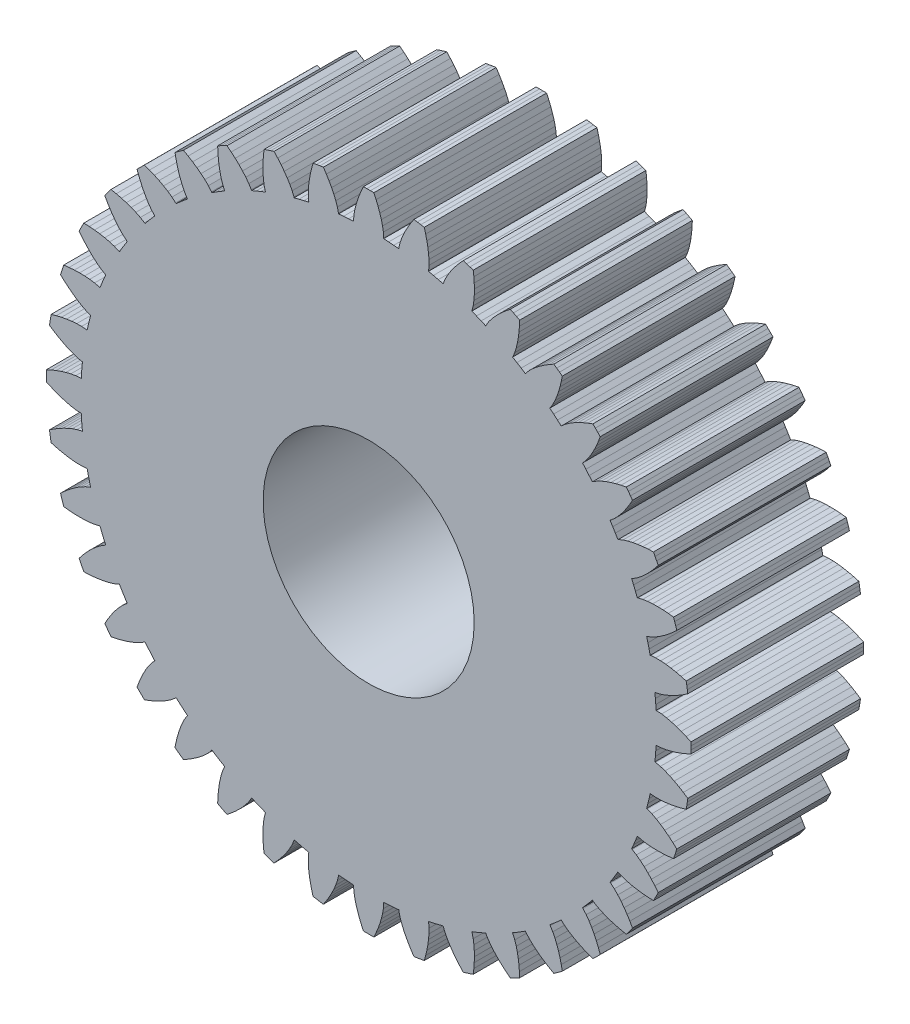
SolidWorks part; units mm, degrees
ref_plane "Спереди" through (0, 0, 0) normal (0, 0, 1) x (1, 0, 0)
ref_plane "Сверху" through (0, 0, 0) normal (0, 1, 0) x (1, 0, 0)
ref_plane "Справа" through (0, 0, 0) normal (1, 0, 0) x (0, 0, -1)
sketch "Эскиз1" plane through (0, 0, 0) normal (0, 0, 1) x (1, 0, 0)
  line L0 (29.959, -1.5683) -> (30.029, -1.5719)
  line L1 (30.029, -1.5719) -> (30.5358, -1.5362)
  line L2 (30.5358, -1.5362) -> (31.045, -1.4475)
  line L3 (31.045, -1.4475) -> (31.5552, -1.3227)
  line L4 (31.5552, -1.3227) -> (32.066, -1.1675)
  line L5 (32.066, -1.1675) -> (32.5766, -0.9849)
  line L6 (32.5766, -0.9849) -> (33.0866, -0.7771)
  line L7 (33.0866, -0.7771) -> (33.5956, -0.5455)
  line L8 (33.5956, -0.5455) -> (33.5995, -0.1818)
  line L9 (33.5995, -0.1818) -> (33.5995, 0.1818)
  line L10 (33.5995, 0.1818) -> (33.5956, 0.5455)
  line L11 (33.5956, 0.5455) -> (33.0866, 0.7771)
  line L12 (33.0866, 0.7771) -> (32.5766, 0.9849)
  line L13 (32.5766, 0.9849) -> (32.066, 1.1675)
  line L14 (32.066, 1.1675) -> (31.5552, 1.3227)
  line L15 (31.5552, 1.3227) -> (31.045, 1.4475)
  line L16 (31.045, 1.4475) -> (30.5358, 1.5362)
  line L17 (30.5358, 1.5362) -> (30.029, 1.5719)
  line L18 (30.029, 1.5719) -> (29.959, 1.5683)
  line L19 (29.959, 1.5683) -> (29.927, 2.0921)
  line L20 (29.927, 2.0921) -> (29.8858, 2.6153)
  line L21 (29.8858, 2.6153) -> (29.8355, 3.1377)
  line L22 (29.8355, 3.1377) -> (29.9052, 3.145)
  line L23 (29.9052, 3.145) -> (30.4002, 3.2595)
  line L24 (30.4002, 3.2595) -> (30.8892, 3.4268)
  line L25 (30.8892, 3.4268) -> (31.3737, 3.6299)
  line L26 (31.3737, 3.6299) -> (31.8538, 3.8631)
  line L27 (31.8538, 3.8631) -> (32.3296, 4.1233)
  line L28 (32.3296, 4.1233) -> (32.8008, 4.4083)
  line L29 (32.8008, 4.4083) -> (33.2673, 4.7167)
  line L30 (33.2673, 4.7167) -> (33.2143, 5.0765)
  line L31 (33.2143, 5.0765) -> (33.1574, 5.4357)
  line L32 (33.1574, 5.4357) -> (33.0966, 5.7943)
  line L33 (33.0966, 5.7943) -> (32.5577, 5.9435)
  line L34 (32.5577, 5.9435) -> (32.0214, 6.0689)
  line L35 (32.0214, 6.0689) -> (31.4885, 6.1693)
  line L36 (31.4885, 6.1693) -> (30.9598, 6.2428)
  line L37 (30.9598, 6.2428) -> (30.4363, 6.2862)
  line L38 (30.4363, 6.2862) -> (29.9195, 6.2942)
  line L39 (29.9195, 6.2942) -> (29.4134, 6.2502)
  line L40 (29.4134, 6.2502) -> (29.3448, 6.2356)
  line L41 (29.3448, 6.2356) -> (29.2312, 6.7479)
  line L42 (29.2312, 6.7479) -> (29.1087, 7.2582)
  line L43 (29.1087, 7.2582) -> (28.9773, 7.7663)
  line L44 (28.9773, 7.7663) -> (29.0451, 7.7845)
  line L45 (29.0451, 7.7845) -> (29.516, 7.975)
  line L46 (29.516, 7.975) -> (29.9728, 8.2167)
  line L47 (29.9728, 8.2167) -> (30.4196, 8.4931)
  line L48 (30.4196, 8.4931) -> (30.8573, 8.7986)
  line L49 (30.8573, 8.7986) -> (31.2865, 9.13)
  line L50 (31.2865, 9.13) -> (31.7074, 9.4852)
  line L51 (31.7074, 9.4852) -> (32.1199, 9.8628)
  line L52 (32.1199, 9.8628) -> (32.0112, 10.2099)
  line L53 (32.0112, 10.2099) -> (31.8988, 10.5558)
  line L54 (31.8988, 10.5558) -> (31.7827, 10.9004)
  line L55 (31.7827, 10.9004) -> (31.2271, 10.9634)
  line L56 (31.2271, 10.9634) -> (30.6778, 11.0035)
  line L57 (30.6778, 11.0035) -> (30.1358, 11.0193)
  line L58 (30.1358, 11.0193) -> (29.6021, 11.0091)
  line L59 (29.6021, 11.0091) -> (29.0782, 10.9701)
  line L60 (29.0782, 10.9701) -> (28.5666, 10.8971)
  line L61 (28.5666, 10.8971) -> (28.0736, 10.7745)
  line L62 (28.0736, 10.7745) -> (28.0081, 10.7493)
  line L63 (28.0081, 10.7493) -> (27.8157, 11.2376)
  line L64 (27.8157, 11.2376) -> (27.6149, 11.7225)
  line L65 (27.6149, 11.7225) -> (27.4056, 12.2038)
  line L66 (27.4056, 12.2038) -> (27.4697, 12.2323)
  line L67 (27.4697, 12.2323) -> (27.905, 12.4942)
  line L68 (27.905, 12.4942) -> (28.3184, 12.8043)
  line L69 (28.3184, 12.8043) -> (28.7164, 13.1472)
  line L70 (28.7164, 13.1472) -> (29.101, 13.5174)
  line L71 (29.101, 13.5174) -> (29.4731, 13.9119)
  line L72 (29.4731, 13.9119) -> (29.8332, 14.3286)
  line L73 (29.8332, 14.3286) -> (30.1815, 14.766)
  line L74 (30.1815, 14.766) -> (30.0199, 15.0918)
  line L75 (30.0199, 15.0918) -> (29.8548, 15.4159)
  line L76 (29.8548, 15.4159) -> (29.6862, 15.7381)
  line L77 (29.6862, 15.7381) -> (29.1276, 15.7135)
  line L78 (29.1276, 15.7135) -> (28.5788, 15.6671)
  line L79 (28.5788, 15.6671) -> (28.041, 15.5979)
  line L80 (28.041, 15.5979) -> (27.5154, 15.5043)
  line L81 (27.5154, 15.5043) -> (27.0041, 15.3839)
  line L82 (27.0041, 15.3839) -> (26.5102, 15.2318)
  line L83 (26.5102, 15.2318) -> (26.0424, 15.0335)
  line L84 (26.0424, 15.0335) -> (25.9817, 14.9984)
  line L85 (25.9817, 14.9984) -> (25.7153, 15.4506)
  line L86 (25.7153, 15.4506) -> (25.4411, 15.8981)
  line L87 (25.4411, 15.8981) -> (25.1591, 16.3407)
  line L88 (25.1591, 16.3407) -> (25.218, 16.3789)
  line L89 (25.218, 16.3789) -> (25.607, 16.7057)
  line L90 (25.607, 16.7057) -> (25.9667, 17.0767)
  line L91 (25.9667, 17.0767) -> (26.3062, 17.4776)
  line L92 (26.3062, 17.4776) -> (26.6281, 17.9034)
  line L93 (26.6281, 17.9034) -> (26.934, 18.3512)
  line L94 (26.934, 18.3512) -> (27.2244, 18.8191)
  line L95 (27.2244, 18.8191) -> (27.5, 19.3057)
  line L96 (27.5, 19.3057) -> (27.2895, 19.6022)
  line L97 (27.2895, 19.6022) -> (27.0757, 19.8964)
  line L98 (27.0757, 19.8964) -> (26.8587, 20.1883)
  line L99 (26.8587, 20.1883) -> (26.3108, 20.0765)
  line L100 (26.3108, 20.0765) -> (25.7761, 19.9449)
  line L101 (25.7761, 19.9449) -> (25.2557, 19.7924)
  line L102 (25.2557, 19.7924) -> (24.7512, 19.6178)
  line L103 (24.7512, 19.6178) -> (24.2651, 19.4189)
  line L104 (24.2651, 19.4189) -> (23.801, 19.1913)
  line L105 (23.801, 19.1913) -> (23.3701, 18.9224)
  line L106 (23.3701, 18.9224) -> (23.3155, 18.8782)
  line L107 (23.3155, 18.8782) -> (22.9817, 19.2832)
  line L108 (22.9817, 19.2832) -> (22.6409, 19.6822)
  line L109 (22.6409, 19.6822) -> (22.2931, 20.0753)
  line L110 (22.2931, 20.0753) -> (22.3453, 20.1222)
  line L111 (22.3453, 20.1222) -> (22.6784, 20.5058)
  line L112 (22.6784, 20.5058) -> (22.9757, 20.9285)
  line L113 (22.9757, 20.9285) -> (23.2482, 21.3776)
  line L114 (23.2482, 21.3776) -> (23.4996, 21.8485)
  line L115 (23.4996, 21.8485) -> (23.7316, 22.3387)
  line L116 (23.7316, 22.3387) -> (23.9453, 22.8462)
  line L117 (23.9453, 22.8462) -> (24.1414, 23.3699)
  line L118 (24.1414, 23.3699) -> (23.887, 23.6299)
  line L119 (23.887, 23.6299) -> (23.6299, 23.887)
  line L120 (23.6299, 23.887) -> (23.3699, 24.1414)
  line L121 (23.3699, 24.1414) -> (22.8462, 23.9453)
  line L122 (22.8462, 23.9453) -> (22.3387, 23.7316)
  line L123 (22.3387, 23.7316) -> (21.8485, 23.4996)
  line L124 (21.8485, 23.4996) -> (21.3776, 23.2482)
  line L125 (21.3776, 23.2482) -> (20.9285, 22.9757)
  line L126 (20.9285, 22.9757) -> (20.5058, 22.6784)
  line L127 (20.5058, 22.6784) -> (20.1222, 22.3453)
  line L128 (20.1222, 22.3453) -> (20.0753, 22.2931)
  line L129 (20.0753, 22.2931) -> (19.6822, 22.6409)
  line L130 (19.6822, 22.6409) -> (19.2832, 22.9817)
  line L131 (19.2832, 22.9817) -> (18.8782, 23.3155)
  line L132 (18.8782, 23.3155) -> (18.9224, 23.3701)
  line L133 (18.9224, 23.3701) -> (19.1913, 23.801)
  line L134 (19.1913, 23.801) -> (19.4189, 24.2651)
  line L135 (19.4189, 24.2651) -> (19.6178, 24.7512)
  line L136 (19.6178, 24.7512) -> (19.7924, 25.2557)
  line L137 (19.7924, 25.2557) -> (19.9449, 25.7761)
  line L138 (19.9449, 25.7761) -> (20.0765, 26.3108)
  line L139 (20.0765, 26.3108) -> (20.1883, 26.8587)
  line L140 (20.1883, 26.8587) -> (19.8964, 27.0757)
  line L141 (19.8964, 27.0757) -> (19.6022, 27.2895)
  line L142 (19.6022, 27.2895) -> (19.3057, 27.5)
  line L143 (19.3057, 27.5) -> (18.8191, 27.2244)
  line L144 (18.8191, 27.2244) -> (18.3512, 26.934)
  line L145 (18.3512, 26.934) -> (17.9034, 26.6281)
  line L146 (17.9034, 26.6281) -> (17.4776, 26.3062)
  line L147 (17.4776, 26.3062) -> (17.0767, 25.9667)
  line L148 (17.0767, 25.9667) -> (16.7057, 25.607)
  line L149 (16.7057, 25.607) -> (16.3789, 25.218)
  line L150 (16.3789, 25.218) -> (16.3407, 25.1591)
  line L151 (16.3407, 25.1591) -> (15.8981, 25.4411)
  line L152 (15.8981, 25.4411) -> (15.4506, 25.7153)
  line L153 (15.4506, 25.7153) -> (14.9984, 25.9817)
  line L154 (14.9984, 25.9817) -> (15.0335, 26.0424)
  line L155 (15.0335, 26.0424) -> (15.2318, 26.5102)
  line L156 (15.2318, 26.5102) -> (15.3839, 27.0041)
  line L157 (15.3839, 27.0041) -> (15.5043, 27.5154)
  line L158 (15.5043, 27.5154) -> (15.5979, 28.041)
  line L159 (15.5979, 28.041) -> (15.6671, 28.5788)
  line L160 (15.6671, 28.5788) -> (15.7135, 29.1276)
  line L161 (15.7135, 29.1276) -> (15.7381, 29.6862)
  line L162 (15.7381, 29.6862) -> (15.4159, 29.8548)
  line L163 (15.4159, 29.8548) -> (15.0918, 30.0199)
  line L164 (15.0918, 30.0199) -> (14.766, 30.1815)
  line L165 (14.766, 30.1815) -> (14.3286, 29.8332)
  line L166 (14.3286, 29.8332) -> (13.9119, 29.4731)
  line L167 (13.9119, 29.4731) -> (13.5174, 29.101)
  line L168 (13.5174, 29.101) -> (13.1472, 28.7164)
  line L169 (13.1472, 28.7164) -> (12.8043, 28.3184)
  line L170 (12.8043, 28.3184) -> (12.4942, 27.905)
  line L171 (12.4942, 27.905) -> (12.2323, 27.4697)
  line L172 (12.2323, 27.4697) -> (12.2038, 27.4056)
  line L173 (12.2038, 27.4056) -> (11.7225, 27.6149)
  line L174 (11.7225, 27.6149) -> (11.2376, 27.8157)
  line L175 (11.2376, 27.8157) -> (10.7493, 28.0081)
  line L176 (10.7493, 28.0081) -> (10.7745, 28.0736)
  line L177 (10.7745, 28.0736) -> (10.8971, 28.5666)
  line L178 (10.8971, 28.5666) -> (10.9701, 29.0782)
  line L179 (10.9701, 29.0782) -> (11.0091, 29.6021)
  line L180 (11.0091, 29.6021) -> (11.0193, 30.1358)
  line L181 (11.0193, 30.1358) -> (11.0035, 30.6778)
  line L182 (11.0035, 30.6778) -> (10.9634, 31.2271)
  line L183 (10.9634, 31.2271) -> (10.9004, 31.7827)
  line L184 (10.9004, 31.7827) -> (10.5558, 31.8988)
  line L185 (10.5558, 31.8988) -> (10.2099, 32.0112)
  line L186 (10.2099, 32.0112) -> (9.8628, 32.1199)
  line L187 (9.8628, 32.1199) -> (9.4852, 31.7074)
  line L188 (9.4852, 31.7074) -> (9.13, 31.2865)
  line L189 (9.13, 31.2865) -> (8.7986, 30.8573)
  line L190 (8.7986, 30.8573) -> (8.4931, 30.4196)
  line L191 (8.4931, 30.4196) -> (8.2167, 29.9728)
  line L192 (8.2167, 29.9728) -> (7.975, 29.516)
  line L193 (7.975, 29.516) -> (7.7845, 29.0451)
  line L194 (7.7845, 29.0451) -> (7.7663, 28.9773)
  line L195 (7.7663, 28.9773) -> (7.2582, 29.1087)
  line L196 (7.2582, 29.1087) -> (6.7479, 29.2312)
  line L197 (6.7479, 29.2312) -> (6.2356, 29.3448)
  line L198 (6.2356, 29.3448) -> (6.2502, 29.4134)
  line L199 (6.2502, 29.4134) -> (6.2942, 29.9195)
  line L200 (6.2942, 29.9195) -> (6.2862, 30.4363)
  line L201 (6.2862, 30.4363) -> (6.2428, 30.9598)
  line L202 (6.2428, 30.9598) -> (6.1693, 31.4885)
  line L203 (6.1693, 31.4885) -> (6.0689, 32.0214)
  line L204 (6.0689, 32.0214) -> (5.9435, 32.5577)
  line L205 (5.9435, 32.5577) -> (5.7943, 33.0966)
  line L206 (5.7943, 33.0966) -> (5.4357, 33.1574)
  line L207 (5.4357, 33.1574) -> (5.0765, 33.2143)
  line L208 (5.0765, 33.2143) -> (4.7167, 33.2673)
  line L209 (4.7167, 33.2673) -> (4.4083, 32.8008)
  line L210 (4.4083, 32.8008) -> (4.1233, 32.3296)
  line L211 (4.1233, 32.3296) -> (3.8631, 31.8538)
  line L212 (3.8631, 31.8538) -> (3.6299, 31.3737)
  line L213 (3.6299, 31.3737) -> (3.4268, 30.8892)
  line L214 (3.4268, 30.8892) -> (3.2595, 30.4002)
  line L215 (3.2595, 30.4002) -> (3.145, 29.9052)
  line L216 (3.145, 29.9052) -> (3.1377, 29.8355)
  line L217 (3.1377, 29.8355) -> (2.6153, 29.8858)
  line L218 (2.6153, 29.8858) -> (2.0921, 29.927)
  line L219 (2.0921, 29.927) -> (1.5683, 29.959)
  line L220 (1.5683, 29.959) -> (1.5719, 30.029)
  line L221 (1.5719, 30.029) -> (1.5362, 30.5358)
  line L222 (1.5362, 30.5358) -> (1.4475, 31.045)
  line L223 (1.4475, 31.045) -> (1.3227, 31.5552)
  line L224 (1.3227, 31.5552) -> (1.1675, 32.066)
  line L225 (1.1675, 32.066) -> (0.9849, 32.5766)
  line L226 (0.9849, 32.5766) -> (0.7771, 33.0866)
  line L227 (0.7771, 33.0866) -> (0.5455, 33.5956)
  line L228 (0.5455, 33.5956) -> (0.1818, 33.5995)
  line L229 (0.1818, 33.5995) -> (-0.1818, 33.5995)
  line L230 (-0.1818, 33.5995) -> (-0.5455, 33.5956)
  line L231 (-0.5455, 33.5956) -> (-0.7771, 33.0866)
  line L232 (-0.7771, 33.0866) -> (-0.9849, 32.5766)
  line L233 (-0.9849, 32.5766) -> (-1.1675, 32.066)
  line L234 (-1.1675, 32.066) -> (-1.3227, 31.5552)
  line L235 (-1.3227, 31.5552) -> (-1.4475, 31.045)
  line L236 (-1.4475, 31.045) -> (-1.5362, 30.5358)
  line L237 (-1.5362, 30.5358) -> (-1.5719, 30.029)
  line L238 (-1.5719, 30.029) -> (-1.5683, 29.959)
  line L239 (-1.5683, 29.959) -> (-2.0921, 29.927)
  line L240 (-2.0921, 29.927) -> (-2.6153, 29.8858)
  line L241 (-2.6153, 29.8858) -> (-3.1377, 29.8355)
  line L242 (-3.1377, 29.8355) -> (-3.145, 29.9052)
  line L243 (-3.145, 29.9052) -> (-3.2595, 30.4002)
  line L244 (-3.2595, 30.4002) -> (-3.4268, 30.8892)
  line L245 (-3.4268, 30.8892) -> (-3.6299, 31.3737)
  line L246 (-3.6299, 31.3737) -> (-3.8631, 31.8538)
  line L247 (-3.8631, 31.8538) -> (-4.1233, 32.3296)
  line L248 (-4.1233, 32.3296) -> (-4.4083, 32.8008)
  line L249 (-4.4083, 32.8008) -> (-4.7167, 33.2673)
  line L250 (-4.7167, 33.2673) -> (-5.0765, 33.2143)
  line L251 (-5.0765, 33.2143) -> (-5.4357, 33.1574)
  line L252 (-5.4357, 33.1574) -> (-5.7943, 33.0966)
  line L253 (-5.7943, 33.0966) -> (-5.9435, 32.5577)
  line L254 (-5.9435, 32.5577) -> (-6.0689, 32.0214)
  line L255 (-6.0689, 32.0214) -> (-6.1693, 31.4885)
  line L256 (-6.1693, 31.4885) -> (-6.2428, 30.9598)
  line L257 (-6.2428, 30.9598) -> (-6.2862, 30.4363)
  line L258 (-6.2862, 30.4363) -> (-6.2942, 29.9195)
  line L259 (-6.2942, 29.9195) -> (-6.2502, 29.4134)
  line L260 (-6.2502, 29.4134) -> (-6.2356, 29.3448)
  line L261 (-6.2356, 29.3448) -> (-6.7479, 29.2312)
  line L262 (-6.7479, 29.2312) -> (-7.2582, 29.1087)
  line L263 (-7.2582, 29.1087) -> (-7.7663, 28.9773)
  line L264 (-7.7663, 28.9773) -> (-7.7845, 29.0451)
  line L265 (-7.7845, 29.0451) -> (-7.975, 29.516)
  line L266 (-7.975, 29.516) -> (-8.2167, 29.9728)
  line L267 (-8.2167, 29.9728) -> (-8.4931, 30.4196)
  line L268 (-8.4931, 30.4196) -> (-8.7986, 30.8573)
  line L269 (-8.7986, 30.8573) -> (-9.13, 31.2865)
  line L270 (-9.13, 31.2865) -> (-9.4852, 31.7074)
  line L271 (-9.4852, 31.7074) -> (-9.8628, 32.1199)
  line L272 (-9.8628, 32.1199) -> (-10.2099, 32.0112)
  line L273 (-10.2099, 32.0112) -> (-10.5558, 31.8988)
  line L274 (-10.5558, 31.8988) -> (-10.9004, 31.7827)
  line L275 (-10.9004, 31.7827) -> (-10.9634, 31.2271)
  line L276 (-10.9634, 31.2271) -> (-11.0035, 30.6778)
  line L277 (-11.0035, 30.6778) -> (-11.0193, 30.1358)
  line L278 (-11.0193, 30.1358) -> (-11.0091, 29.6021)
  line L279 (-11.0091, 29.6021) -> (-10.9701, 29.0782)
  line L280 (-10.9701, 29.0782) -> (-10.8971, 28.5666)
  line L281 (-10.8971, 28.5666) -> (-10.7745, 28.0736)
  line L282 (-10.7745, 28.0736) -> (-10.7493, 28.0081)
  line L283 (-10.7493, 28.0081) -> (-11.2376, 27.8157)
  line L284 (-11.2376, 27.8157) -> (-11.7225, 27.6149)
  line L285 (-11.7225, 27.6149) -> (-12.2038, 27.4056)
  line L286 (-12.2038, 27.4056) -> (-12.2323, 27.4697)
  line L287 (-12.2323, 27.4697) -> (-12.4942, 27.905)
  line L288 (-12.4942, 27.905) -> (-12.8043, 28.3184)
  line L289 (-12.8043, 28.3184) -> (-13.1472, 28.7164)
  line L290 (-13.1472, 28.7164) -> (-13.5174, 29.101)
  line L291 (-13.5174, 29.101) -> (-13.9119, 29.4731)
  line L292 (-13.9119, 29.4731) -> (-14.3286, 29.8332)
  line L293 (-14.3286, 29.8332) -> (-14.766, 30.1815)
  line L294 (-14.766, 30.1815) -> (-15.0918, 30.0199)
  line L295 (-15.0918, 30.0199) -> (-15.4159, 29.8548)
  line L296 (-15.4159, 29.8548) -> (-15.7381, 29.6862)
  line L297 (-15.7381, 29.6862) -> (-15.7135, 29.1276)
  line L298 (-15.7135, 29.1276) -> (-15.6671, 28.5788)
  line L299 (-15.6671, 28.5788) -> (-15.5979, 28.041)
  line L300 (-15.5979, 28.041) -> (-15.5043, 27.5154)
  line L301 (-15.5043, 27.5154) -> (-15.3839, 27.0041)
  line L302 (-15.3839, 27.0041) -> (-15.2318, 26.5102)
  line L303 (-15.2318, 26.5102) -> (-15.0335, 26.0424)
  line L304 (-15.0335, 26.0424) -> (-14.9984, 25.9817)
  line L305 (-14.9984, 25.9817) -> (-15.4506, 25.7153)
  line L306 (-15.4506, 25.7153) -> (-15.8981, 25.4411)
  line L307 (-15.8981, 25.4411) -> (-16.3407, 25.1591)
  line L308 (-16.3407, 25.1591) -> (-16.3789, 25.218)
  line L309 (-16.3789, 25.218) -> (-16.7057, 25.607)
  line L310 (-16.7057, 25.607) -> (-17.0767, 25.9667)
  line L311 (-17.0767, 25.9667) -> (-17.4776, 26.3062)
  line L312 (-17.4776, 26.3062) -> (-17.9034, 26.6281)
  line L313 (-17.9034, 26.6281) -> (-18.3512, 26.934)
  line L314 (-18.3512, 26.934) -> (-18.8191, 27.2244)
  line L315 (-18.8191, 27.2244) -> (-19.3057, 27.5)
  line L316 (-19.3057, 27.5) -> (-19.6022, 27.2895)
  line L317 (-19.6022, 27.2895) -> (-19.8964, 27.0757)
  line L318 (-19.8964, 27.0757) -> (-20.1883, 26.8587)
  line L319 (-20.1883, 26.8587) -> (-20.0765, 26.3108)
  line L320 (-20.0765, 26.3108) -> (-19.9449, 25.7761)
  line L321 (-19.9449, 25.7761) -> (-19.7924, 25.2557)
  line L322 (-19.7924, 25.2557) -> (-19.6178, 24.7512)
  line L323 (-19.6178, 24.7512) -> (-19.4189, 24.2651)
  line L324 (-19.4189, 24.2651) -> (-19.1913, 23.801)
  line L325 (-19.1913, 23.801) -> (-18.9224, 23.3701)
  line L326 (-18.9224, 23.3701) -> (-18.8782, 23.3155)
  line L327 (-18.8782, 23.3155) -> (-19.2832, 22.9817)
  line L328 (-19.2832, 22.9817) -> (-19.6822, 22.6409)
  line L329 (-19.6822, 22.6409) -> (-20.0753, 22.2931)
  line L330 (-20.0753, 22.2931) -> (-20.1222, 22.3453)
  line L331 (-20.1222, 22.3453) -> (-20.5058, 22.6784)
  line L332 (-20.5058, 22.6784) -> (-20.9285, 22.9757)
  line L333 (-20.9285, 22.9757) -> (-21.3776, 23.2482)
  line L334 (-21.3776, 23.2482) -> (-21.8485, 23.4996)
  line L335 (-21.8485, 23.4996) -> (-22.3387, 23.7316)
  line L336 (-22.3387, 23.7316) -> (-22.8462, 23.9453)
  line L337 (-22.8462, 23.9453) -> (-23.3699, 24.1414)
  line L338 (-23.3699, 24.1414) -> (-23.6299, 23.887)
  line L339 (-23.6299, 23.887) -> (-23.887, 23.6299)
  line L340 (-23.887, 23.6299) -> (-24.1414, 23.3699)
  line L341 (-24.1414, 23.3699) -> (-23.9453, 22.8462)
  line L342 (-23.9453, 22.8462) -> (-23.7316, 22.3387)
  line L343 (-23.7316, 22.3387) -> (-23.4996, 21.8485)
  line L344 (-23.4996, 21.8485) -> (-23.2482, 21.3776)
  line L345 (-23.2482, 21.3776) -> (-22.9757, 20.9285)
  line L346 (-22.9757, 20.9285) -> (-22.6784, 20.5058)
  line L347 (-22.6784, 20.5058) -> (-22.3453, 20.1222)
  line L348 (-22.3453, 20.1222) -> (-22.2931, 20.0753)
  line L349 (-22.2931, 20.0753) -> (-22.6409, 19.6822)
  line L350 (-22.6409, 19.6822) -> (-22.9817, 19.2832)
  line L351 (-22.9817, 19.2832) -> (-23.3155, 18.8782)
  line L352 (-23.3155, 18.8782) -> (-23.3701, 18.9224)
  line L353 (-23.3701, 18.9224) -> (-23.801, 19.1913)
  line L354 (-23.801, 19.1913) -> (-24.2651, 19.4189)
  line L355 (-24.2651, 19.4189) -> (-24.7512, 19.6178)
  line L356 (-24.7512, 19.6178) -> (-25.2557, 19.7924)
  line L357 (-25.2557, 19.7924) -> (-25.7761, 19.9449)
  line L358 (-25.7761, 19.9449) -> (-26.3108, 20.0765)
  line L359 (-26.3108, 20.0765) -> (-26.8587, 20.1883)
  line L360 (-26.8587, 20.1883) -> (-27.0757, 19.8964)
  line L361 (-27.0757, 19.8964) -> (-27.2895, 19.6022)
  line L362 (-27.2895, 19.6022) -> (-27.5, 19.3057)
  line L363 (-27.5, 19.3057) -> (-27.2244, 18.8191)
  line L364 (-27.2244, 18.8191) -> (-26.934, 18.3512)
  line L365 (-26.934, 18.3512) -> (-26.6281, 17.9034)
  line L366 (-26.6281, 17.9034) -> (-26.3062, 17.4776)
  line L367 (-26.3062, 17.4776) -> (-25.9667, 17.0767)
  line L368 (-25.9667, 17.0767) -> (-25.607, 16.7057)
  line L369 (-25.607, 16.7057) -> (-25.218, 16.3789)
  line L370 (-25.218, 16.3789) -> (-25.1591, 16.3407)
  line L371 (-25.1591, 16.3407) -> (-25.4411, 15.8981)
  line L372 (-25.4411, 15.8981) -> (-25.7153, 15.4506)
  line L373 (-25.7153, 15.4506) -> (-25.9817, 14.9984)
  line L374 (-25.9817, 14.9984) -> (-26.0424, 15.0335)
  line L375 (-26.0424, 15.0335) -> (-26.5102, 15.2318)
  line L376 (-26.5102, 15.2318) -> (-27.0041, 15.3839)
  line L377 (-27.0041, 15.3839) -> (-27.5154, 15.5043)
  line L378 (-27.5154, 15.5043) -> (-28.041, 15.5979)
  line L379 (-28.041, 15.5979) -> (-28.5788, 15.6671)
  line L380 (-28.5788, 15.6671) -> (-29.1276, 15.7135)
  line L381 (-29.1276, 15.7135) -> (-29.6862, 15.7381)
  line L382 (-29.6862, 15.7381) -> (-29.8548, 15.4159)
  line L383 (-29.8548, 15.4159) -> (-30.0199, 15.0918)
  line L384 (-30.0199, 15.0918) -> (-30.1815, 14.766)
  line L385 (-30.1815, 14.766) -> (-29.8332, 14.3286)
  line L386 (-29.8332, 14.3286) -> (-29.4731, 13.9119)
  line L387 (-29.4731, 13.9119) -> (-29.101, 13.5174)
  line L388 (-29.101, 13.5174) -> (-28.7164, 13.1472)
  line L389 (-28.7164, 13.1472) -> (-28.3184, 12.8043)
  line L390 (-28.3184, 12.8043) -> (-27.905, 12.4942)
  line L391 (-27.905, 12.4942) -> (-27.4697, 12.2323)
  line L392 (-27.4697, 12.2323) -> (-27.4056, 12.2038)
  line L393 (-27.4056, 12.2038) -> (-27.6149, 11.7225)
  line L394 (-27.6149, 11.7225) -> (-27.8157, 11.2376)
  line L395 (-27.8157, 11.2376) -> (-28.0081, 10.7493)
  line L396 (-28.0081, 10.7493) -> (-28.0736, 10.7745)
  line L397 (-28.0736, 10.7745) -> (-28.5666, 10.8971)
  line L398 (-28.5666, 10.8971) -> (-29.0782, 10.9701)
  line L399 (-29.0782, 10.9701) -> (-29.6021, 11.0091)
  line L400 (-29.6021, 11.0091) -> (-30.1358, 11.0193)
  line L401 (-30.1358, 11.0193) -> (-30.6778, 11.0035)
  line L402 (-30.6778, 11.0035) -> (-31.2271, 10.9634)
  line L403 (-31.2271, 10.9634) -> (-31.7827, 10.9004)
  line L404 (-31.7827, 10.9004) -> (-31.8988, 10.5558)
  line L405 (-31.8988, 10.5558) -> (-32.0112, 10.2099)
  line L406 (-32.0112, 10.2099) -> (-32.1199, 9.8628)
  line L407 (-32.1199, 9.8628) -> (-31.7074, 9.4852)
  line L408 (-31.7074, 9.4852) -> (-31.2865, 9.13)
  line L409 (-31.2865, 9.13) -> (-30.8573, 8.7986)
  line L410 (-30.8573, 8.7986) -> (-30.4196, 8.4931)
  line L411 (-30.4196, 8.4931) -> (-29.9728, 8.2167)
  line L412 (-29.9728, 8.2167) -> (-29.516, 7.975)
  line L413 (-29.516, 7.975) -> (-29.0451, 7.7845)
  line L414 (-29.0451, 7.7845) -> (-28.9773, 7.7663)
  line L415 (-28.9773, 7.7663) -> (-29.1087, 7.2582)
  line L416 (-29.1087, 7.2582) -> (-29.2312, 6.7479)
  line L417 (-29.2312, 6.7479) -> (-29.3448, 6.2356)
  line L418 (-29.3448, 6.2356) -> (-29.4134, 6.2502)
  line L419 (-29.4134, 6.2502) -> (-29.9195, 6.2942)
  line L420 (-29.9195, 6.2942) -> (-30.4363, 6.2862)
  line L421 (-30.4363, 6.2862) -> (-30.9598, 6.2428)
  line L422 (-30.9598, 6.2428) -> (-31.4885, 6.1693)
  line L423 (-31.4885, 6.1693) -> (-32.0214, 6.0689)
  line L424 (-32.0214, 6.0689) -> (-32.5577, 5.9435)
  line L425 (-32.5577, 5.9435) -> (-33.0966, 5.7943)
  line L426 (-33.0966, 5.7943) -> (-33.1574, 5.4357)
  line L427 (-33.1574, 5.4357) -> (-33.2143, 5.0765)
  line L428 (-33.2143, 5.0765) -> (-33.2673, 4.7167)
  line L429 (-33.2673, 4.7167) -> (-32.8008, 4.4083)
  line L430 (-32.8008, 4.4083) -> (-32.3296, 4.1233)
  line L431 (-32.3296, 4.1233) -> (-31.8538, 3.8631)
  line L432 (-31.8538, 3.8631) -> (-31.3737, 3.6299)
  line L433 (-31.3737, 3.6299) -> (-30.8892, 3.4268)
  line L434 (-30.8892, 3.4268) -> (-30.4002, 3.2595)
  line L435 (-30.4002, 3.2595) -> (-29.9052, 3.145)
  line L436 (-29.9052, 3.145) -> (-29.8355, 3.1377)
  line L437 (-29.8355, 3.1377) -> (-29.8858, 2.6153)
  line L438 (-29.8858, 2.6153) -> (-29.927, 2.0921)
  line L439 (-29.927, 2.0921) -> (-29.959, 1.5683)
  line L440 (-29.959, 1.5683) -> (-30.029, 1.5719)
  line L441 (-30.029, 1.5719) -> (-30.5358, 1.5362)
  line L442 (-30.5358, 1.5362) -> (-31.045, 1.4475)
  line L443 (-31.045, 1.4475) -> (-31.5552, 1.3227)
  line L444 (-31.5552, 1.3227) -> (-32.066, 1.1675)
  line L445 (-32.066, 1.1675) -> (-32.5766, 0.9849)
  line L446 (-32.5766, 0.9849) -> (-33.0866, 0.7771)
  line L447 (-33.0866, 0.7771) -> (-33.5956, 0.5455)
  line L448 (-33.5956, 0.5455) -> (-33.5995, 0.1818)
  line L449 (-33.5995, 0.1818) -> (-33.5995, -0.1818)
  line L450 (-33.5995, -0.1818) -> (-33.5956, -0.5455)
  line L451 (-33.5956, -0.5455) -> (-33.0866, -0.7771)
  line L452 (-33.0866, -0.7771) -> (-32.5766, -0.9849)
  line L453 (-32.5766, -0.9849) -> (-32.066, -1.1675)
  line L454 (-32.066, -1.1675) -> (-31.5552, -1.3227)
  line L455 (-31.5552, -1.3227) -> (-31.045, -1.4475)
  line L456 (-31.045, -1.4475) -> (-30.5358, -1.5362)
  line L457 (-30.5358, -1.5362) -> (-30.029, -1.5719)
  line L458 (-30.029, -1.5719) -> (-29.959, -1.5683)
  line L459 (-29.959, -1.5683) -> (-29.927, -2.0921)
  line L460 (-29.927, -2.0921) -> (-29.8858, -2.6153)
  line L461 (-29.8858, -2.6153) -> (-29.8355, -3.1377)
  line L462 (-29.8355, -3.1377) -> (-29.9052, -3.145)
  line L463 (-29.9052, -3.145) -> (-30.4002, -3.2595)
  line L464 (-30.4002, -3.2595) -> (-30.8892, -3.4268)
  line L465 (-30.8892, -3.4268) -> (-31.3737, -3.6299)
  line L466 (-31.3737, -3.6299) -> (-31.8538, -3.8631)
  line L467 (-31.8538, -3.8631) -> (-32.3296, -4.1233)
  line L468 (-32.3296, -4.1233) -> (-32.8008, -4.4083)
  line L469 (-32.8008, -4.4083) -> (-33.2673, -4.7167)
  line L470 (-33.2673, -4.7167) -> (-33.2143, -5.0765)
  line L471 (-33.2143, -5.0765) -> (-33.1574, -5.4357)
  line L472 (-33.1574, -5.4357) -> (-33.0966, -5.7943)
  line L473 (-33.0966, -5.7943) -> (-32.5577, -5.9435)
  line L474 (-32.5577, -5.9435) -> (-32.0214, -6.0689)
  line L475 (-32.0214, -6.0689) -> (-31.4885, -6.1693)
  line L476 (-31.4885, -6.1693) -> (-30.9598, -6.2428)
  line L477 (-30.9598, -6.2428) -> (-30.4363, -6.2862)
  line L478 (-30.4363, -6.2862) -> (-29.9195, -6.2942)
  line L479 (-29.9195, -6.2942) -> (-29.4134, -6.2502)
  line L480 (-29.4134, -6.2502) -> (-29.3448, -6.2356)
  line L481 (-29.3448, -6.2356) -> (-29.2312, -6.7479)
  line L482 (-29.2312, -6.7479) -> (-29.1087, -7.2582)
  line L483 (-29.1087, -7.2582) -> (-28.9773, -7.7663)
  line L484 (-28.9773, -7.7663) -> (-29.0451, -7.7845)
  line L485 (-29.0451, -7.7845) -> (-29.516, -7.975)
  line L486 (-29.516, -7.975) -> (-29.9728, -8.2167)
  line L487 (-29.9728, -8.2167) -> (-30.4196, -8.4931)
  line L488 (-30.4196, -8.4931) -> (-30.8573, -8.7986)
  line L489 (-30.8573, -8.7986) -> (-31.2865, -9.13)
  line L490 (-31.2865, -9.13) -> (-31.7074, -9.4852)
  line L491 (-31.7074, -9.4852) -> (-32.1199, -9.8628)
  line L492 (-32.1199, -9.8628) -> (-32.0112, -10.2099)
  line L493 (-32.0112, -10.2099) -> (-31.8988, -10.5558)
  line L494 (-31.8988, -10.5558) -> (-31.7827, -10.9004)
  line L495 (-31.7827, -10.9004) -> (-31.2271, -10.9634)
  line L496 (-31.2271, -10.9634) -> (-30.6778, -11.0035)
  line L497 (-30.6778, -11.0035) -> (-30.1358, -11.0193)
  line L498 (-30.1358, -11.0193) -> (-29.6021, -11.0091)
  line L499 (-29.6021, -11.0091) -> (-29.0782, -10.9701)
  line L500 (-29.0782, -10.9701) -> (-28.5666, -10.8971)
  line L501 (-28.5666, -10.8971) -> (-28.0736, -10.7745)
  line L502 (-28.0736, -10.7745) -> (-28.0081, -10.7493)
  line L503 (-28.0081, -10.7493) -> (-27.8157, -11.2376)
  line L504 (-27.8157, -11.2376) -> (-27.6149, -11.7225)
  line L505 (-27.6149, -11.7225) -> (-27.4056, -12.2038)
  line L506 (-27.4056, -12.2038) -> (-27.4697, -12.2323)
  line L507 (-27.4697, -12.2323) -> (-27.905, -12.4942)
  line L508 (-27.905, -12.4942) -> (-28.3184, -12.8043)
  line L509 (-28.3184, -12.8043) -> (-28.7164, -13.1472)
  line L510 (-28.7164, -13.1472) -> (-29.101, -13.5174)
  line L511 (-29.101, -13.5174) -> (-29.4731, -13.9119)
  line L512 (-29.4731, -13.9119) -> (-29.8332, -14.3286)
  line L513 (-29.8332, -14.3286) -> (-30.1815, -14.766)
  line L514 (-30.1815, -14.766) -> (-30.0199, -15.0918)
  line L515 (-30.0199, -15.0918) -> (-29.8548, -15.4159)
  line L516 (-29.8548, -15.4159) -> (-29.6862, -15.7381)
  line L517 (-29.6862, -15.7381) -> (-29.1276, -15.7135)
  line L518 (-29.1276, -15.7135) -> (-28.5788, -15.6671)
  line L519 (-28.5788, -15.6671) -> (-28.041, -15.5979)
  line L520 (-28.041, -15.5979) -> (-27.5154, -15.5043)
  line L521 (-27.5154, -15.5043) -> (-27.0041, -15.3839)
  line L522 (-27.0041, -15.3839) -> (-26.5102, -15.2318)
  line L523 (-26.5102, -15.2318) -> (-26.0424, -15.0335)
  line L524 (-26.0424, -15.0335) -> (-25.9817, -14.9984)
  line L525 (-25.9817, -14.9984) -> (-25.7153, -15.4506)
  line L526 (-25.7153, -15.4506) -> (-25.4411, -15.8981)
  line L527 (-25.4411, -15.8981) -> (-25.1591, -16.3407)
  line L528 (-25.1591, -16.3407) -> (-25.218, -16.3789)
  line L529 (-25.218, -16.3789) -> (-25.607, -16.7057)
  line L530 (-25.607, -16.7057) -> (-25.9667, -17.0767)
  line L531 (-25.9667, -17.0767) -> (-26.3062, -17.4776)
  line L532 (-26.3062, -17.4776) -> (-26.6281, -17.9034)
  line L533 (-26.6281, -17.9034) -> (-26.934, -18.3512)
  line L534 (-26.934, -18.3512) -> (-27.2244, -18.8191)
  line L535 (-27.2244, -18.8191) -> (-27.5, -19.3057)
  line L536 (-27.5, -19.3057) -> (-27.2895, -19.6022)
  line L537 (-27.2895, -19.6022) -> (-27.0757, -19.8964)
  line L538 (-27.0757, -19.8964) -> (-26.8587, -20.1883)
  line L539 (-26.8587, -20.1883) -> (-26.3108, -20.0765)
  line L540 (-26.3108, -20.0765) -> (-25.7761, -19.9449)
  line L541 (-25.7761, -19.9449) -> (-25.2557, -19.7924)
  line L542 (-25.2557, -19.7924) -> (-24.7512, -19.6178)
  line L543 (-24.7512, -19.6178) -> (-24.2651, -19.4189)
  line L544 (-24.2651, -19.4189) -> (-23.801, -19.1913)
  line L545 (-23.801, -19.1913) -> (-23.3701, -18.9224)
  line L546 (-23.3701, -18.9224) -> (-23.3155, -18.8782)
  line L547 (-23.3155, -18.8782) -> (-22.9817, -19.2832)
  line L548 (-22.9817, -19.2832) -> (-22.6409, -19.6822)
  line L549 (-22.6409, -19.6822) -> (-22.2931, -20.0753)
  line L550 (-22.2931, -20.0753) -> (-22.3453, -20.1222)
  line L551 (-22.3453, -20.1222) -> (-22.6784, -20.5058)
  line L552 (-22.6784, -20.5058) -> (-22.9757, -20.9285)
  line L553 (-22.9757, -20.9285) -> (-23.2482, -21.3776)
  line L554 (-23.2482, -21.3776) -> (-23.4996, -21.8485)
  line L555 (-23.4996, -21.8485) -> (-23.7316, -22.3387)
  line L556 (-23.7316, -22.3387) -> (-23.9453, -22.8462)
  line L557 (-23.9453, -22.8462) -> (-24.1414, -23.3699)
  line L558 (-24.1414, -23.3699) -> (-23.887, -23.6299)
  line L559 (-23.887, -23.6299) -> (-23.6299, -23.887)
  line L560 (-23.6299, -23.887) -> (-23.3699, -24.1414)
  line L561 (-23.3699, -24.1414) -> (-22.8462, -23.9453)
  line L562 (-22.8462, -23.9453) -> (-22.3387, -23.7316)
  line L563 (-22.3387, -23.7316) -> (-21.8485, -23.4996)
  line L564 (-21.8485, -23.4996) -> (-21.3776, -23.2482)
  line L565 (-21.3776, -23.2482) -> (-20.9285, -22.9757)
  line L566 (-20.9285, -22.9757) -> (-20.5058, -22.6784)
  line L567 (-20.5058, -22.6784) -> (-20.1222, -22.3453)
  line L568 (-20.1222, -22.3453) -> (-20.0753, -22.2931)
  line L569 (-20.0753, -22.2931) -> (-19.6822, -22.6409)
  line L570 (-19.6822, -22.6409) -> (-19.2832, -22.9817)
  line L571 (-19.2832, -22.9817) -> (-18.8782, -23.3155)
  line L572 (-18.8782, -23.3155) -> (-18.9224, -23.3701)
  line L573 (-18.9224, -23.3701) -> (-19.1913, -23.801)
  line L574 (-19.1913, -23.801) -> (-19.4189, -24.2651)
  line L575 (-19.4189, -24.2651) -> (-19.6178, -24.7512)
  line L576 (-19.6178, -24.7512) -> (-19.7924, -25.2557)
  line L577 (-19.7924, -25.2557) -> (-19.9449, -25.7761)
  line L578 (-19.9449, -25.7761) -> (-20.0765, -26.3108)
  line L579 (-20.0765, -26.3108) -> (-20.1883, -26.8587)
  line L580 (-20.1883, -26.8587) -> (-19.8964, -27.0757)
  line L581 (-19.8964, -27.0757) -> (-19.6022, -27.2895)
  line L582 (-19.6022, -27.2895) -> (-19.3057, -27.5)
  line L583 (-19.3057, -27.5) -> (-18.8191, -27.2244)
  line L584 (-18.8191, -27.2244) -> (-18.3512, -26.934)
  line L585 (-18.3512, -26.934) -> (-17.9034, -26.6281)
  line L586 (-17.9034, -26.6281) -> (-17.4776, -26.3062)
  line L587 (-17.4776, -26.3062) -> (-17.0767, -25.9667)
  line L588 (-17.0767, -25.9667) -> (-16.7057, -25.607)
  line L589 (-16.7057, -25.607) -> (-16.3789, -25.218)
  line L590 (-16.3789, -25.218) -> (-16.3407, -25.1591)
  line L591 (-16.3407, -25.1591) -> (-15.8981, -25.4411)
  line L592 (-15.8981, -25.4411) -> (-15.4506, -25.7153)
  line L593 (-15.4506, -25.7153) -> (-14.9984, -25.9817)
  line L594 (-14.9984, -25.9817) -> (-15.0335, -26.0424)
  line L595 (-15.0335, -26.0424) -> (-15.2318, -26.5102)
  line L596 (-15.2318, -26.5102) -> (-15.3839, -27.0041)
  line L597 (-15.3839, -27.0041) -> (-15.5043, -27.5154)
  line L598 (-15.5043, -27.5154) -> (-15.5979, -28.041)
  line L599 (-15.5979, -28.041) -> (-15.6671, -28.5788)
  line L600 (-15.6671, -28.5788) -> (-15.7135, -29.1276)
  line L601 (-15.7135, -29.1276) -> (-15.7381, -29.6862)
  line L602 (-15.7381, -29.6862) -> (-15.4159, -29.8548)
  line L603 (-15.4159, -29.8548) -> (-15.0918, -30.0199)
  line L604 (-15.0918, -30.0199) -> (-14.766, -30.1815)
  line L605 (-14.766, -30.1815) -> (-14.3286, -29.8332)
  line L606 (-14.3286, -29.8332) -> (-13.9119, -29.4731)
  line L607 (-13.9119, -29.4731) -> (-13.5174, -29.101)
  line L608 (-13.5174, -29.101) -> (-13.1472, -28.7164)
  line L609 (-13.1472, -28.7164) -> (-12.8043, -28.3184)
  line L610 (-12.8043, -28.3184) -> (-12.4942, -27.905)
  line L611 (-12.4942, -27.905) -> (-12.2323, -27.4697)
  line L612 (-12.2323, -27.4697) -> (-12.2038, -27.4056)
  line L613 (-12.2038, -27.4056) -> (-11.7225, -27.6149)
  line L614 (-11.7225, -27.6149) -> (-11.2376, -27.8157)
  line L615 (-11.2376, -27.8157) -> (-10.7493, -28.0081)
  line L616 (-10.7493, -28.0081) -> (-10.7745, -28.0736)
  line L617 (-10.7745, -28.0736) -> (-10.8971, -28.5666)
  line L618 (-10.8971, -28.5666) -> (-10.9701, -29.0782)
  line L619 (-10.9701, -29.0782) -> (-11.0091, -29.6021)
  line L620 (-11.0091, -29.6021) -> (-11.0193, -30.1358)
  line L621 (-11.0193, -30.1358) -> (-11.0035, -30.6778)
  line L622 (-11.0035, -30.6778) -> (-10.9634, -31.2271)
  line L623 (-10.9634, -31.2271) -> (-10.9004, -31.7827)
  line L624 (-10.9004, -31.7827) -> (-10.5558, -31.8988)
  line L625 (-10.5558, -31.8988) -> (-10.2099, -32.0112)
  line L626 (-10.2099, -32.0112) -> (-9.8628, -32.1199)
  line L627 (-9.8628, -32.1199) -> (-9.4852, -31.7074)
  line L628 (-9.4852, -31.7074) -> (-9.13, -31.2865)
  line L629 (-9.13, -31.2865) -> (-8.7986, -30.8573)
  line L630 (-8.7986, -30.8573) -> (-8.4931, -30.4196)
  line L631 (-8.4931, -30.4196) -> (-8.2167, -29.9728)
  line L632 (-8.2167, -29.9728) -> (-7.975, -29.516)
  line L633 (-7.975, -29.516) -> (-7.7845, -29.0451)
  line L634 (-7.7845, -29.0451) -> (-7.7663, -28.9773)
  line L635 (-7.7663, -28.9773) -> (-7.2582, -29.1087)
  line L636 (-7.2582, -29.1087) -> (-6.7479, -29.2312)
  line L637 (-6.7479, -29.2312) -> (-6.2356, -29.3448)
  line L638 (-6.2356, -29.3448) -> (-6.2502, -29.4134)
  line L639 (-6.2502, -29.4134) -> (-6.2942, -29.9195)
  line L640 (-6.2942, -29.9195) -> (-6.2862, -30.4363)
  line L641 (-6.2862, -30.4363) -> (-6.2428, -30.9598)
  line L642 (-6.2428, -30.9598) -> (-6.1693, -31.4885)
  line L643 (-6.1693, -31.4885) -> (-6.0689, -32.0214)
  line L644 (-6.0689, -32.0214) -> (-5.9435, -32.5577)
  line L645 (-5.9435, -32.5577) -> (-5.7943, -33.0966)
  line L646 (-5.7943, -33.0966) -> (-5.4357, -33.1574)
  line L647 (-5.4357, -33.1574) -> (-5.0765, -33.2143)
  line L648 (-5.0765, -33.2143) -> (-4.7167, -33.2673)
  line L649 (-4.7167, -33.2673) -> (-4.4083, -32.8008)
  line L650 (-4.4083, -32.8008) -> (-4.1233, -32.3296)
  line L651 (-4.1233, -32.3296) -> (-3.8631, -31.8538)
  line L652 (-3.8631, -31.8538) -> (-3.6299, -31.3737)
  line L653 (-3.6299, -31.3737) -> (-3.4268, -30.8892)
  line L654 (-3.4268, -30.8892) -> (-3.2595, -30.4002)
  line L655 (-3.2595, -30.4002) -> (-3.145, -29.9052)
  line L656 (-3.145, -29.9052) -> (-3.1377, -29.8355)
  line L657 (-3.1377, -29.8355) -> (-2.6153, -29.8858)
  line L658 (-2.6153, -29.8858) -> (-2.0921, -29.927)
  line L659 (-2.0921, -29.927) -> (-1.5683, -29.959)
  line L660 (-1.5683, -29.959) -> (-1.5719, -30.029)
  line L661 (-1.5719, -30.029) -> (-1.5362, -30.5358)
  line L662 (-1.5362, -30.5358) -> (-1.4475, -31.045)
  line L663 (-1.4475, -31.045) -> (-1.3227, -31.5552)
  line L664 (-1.3227, -31.5552) -> (-1.1675, -32.066)
  line L665 (-1.1675, -32.066) -> (-0.9849, -32.5766)
  line L666 (-0.9849, -32.5766) -> (-0.7771, -33.0866)
  line L667 (-0.7771, -33.0866) -> (-0.5455, -33.5956)
  line L668 (-0.5455, -33.5956) -> (-0.1818, -33.5995)
  line L669 (-0.1818, -33.5995) -> (0.1818, -33.5995)
  line L670 (0.1818, -33.5995) -> (0.5455, -33.5956)
  line L671 (0.5455, -33.5956) -> (0.7771, -33.0866)
  line L672 (0.7771, -33.0866) -> (0.9849, -32.5766)
  line L673 (0.9849, -32.5766) -> (1.1675, -32.066)
  line L674 (1.1675, -32.066) -> (1.3227, -31.5552)
  line L675 (1.3227, -31.5552) -> (1.4475, -31.045)
  line L676 (1.4475, -31.045) -> (1.5362, -30.5358)
  line L677 (1.5362, -30.5358) -> (1.5719, -30.029)
  line L678 (1.5719, -30.029) -> (1.5683, -29.959)
  line L679 (1.5683, -29.959) -> (2.0921, -29.927)
  line L680 (2.0921, -29.927) -> (2.6153, -29.8858)
  line L681 (2.6153, -29.8858) -> (3.1377, -29.8355)
  line L682 (3.1377, -29.8355) -> (3.145, -29.9052)
  line L683 (3.145, -29.9052) -> (3.2595, -30.4002)
  line L684 (3.2595, -30.4002) -> (3.4268, -30.8892)
  line L685 (3.4268, -30.8892) -> (3.6299, -31.3737)
  line L686 (3.6299, -31.3737) -> (3.8631, -31.8538)
  line L687 (3.8631, -31.8538) -> (4.1233, -32.3296)
  line L688 (4.1233, -32.3296) -> (4.4083, -32.8008)
  line L689 (4.4083, -32.8008) -> (4.7167, -33.2673)
  line L690 (4.7167, -33.2673) -> (5.0765, -33.2143)
  line L691 (5.0765, -33.2143) -> (5.4357, -33.1574)
  line L692 (5.4357, -33.1574) -> (5.7943, -33.0966)
  line L693 (5.7943, -33.0966) -> (5.9435, -32.5577)
  line L694 (5.9435, -32.5577) -> (6.0689, -32.0214)
  line L695 (6.0689, -32.0214) -> (6.1693, -31.4885)
  line L696 (6.1693, -31.4885) -> (6.2428, -30.9598)
  line L697 (6.2428, -30.9598) -> (6.2862, -30.4363)
  line L698 (6.2862, -30.4363) -> (6.2942, -29.9195)
  line L699 (6.2942, -29.9195) -> (6.2502, -29.4134)
  line L700 (6.2502, -29.4134) -> (6.2356, -29.3448)
  line L701 (6.2356, -29.3448) -> (6.7479, -29.2312)
  line L702 (6.7479, -29.2312) -> (7.2582, -29.1087)
  line L703 (7.2582, -29.1087) -> (7.7663, -28.9773)
  line L704 (7.7663, -28.9773) -> (7.7845, -29.0451)
  line L705 (7.7845, -29.0451) -> (7.975, -29.516)
  line L706 (7.975, -29.516) -> (8.2167, -29.9728)
  line L707 (8.2167, -29.9728) -> (8.4931, -30.4196)
  line L708 (8.4931, -30.4196) -> (8.7986, -30.8573)
  line L709 (8.7986, -30.8573) -> (9.13, -31.2865)
  line L710 (9.13, -31.2865) -> (9.4852, -31.7074)
  line L711 (9.4852, -31.7074) -> (9.8628, -32.1199)
  line L712 (9.8628, -32.1199) -> (10.2099, -32.0112)
  line L713 (10.2099, -32.0112) -> (10.5558, -31.8988)
  line L714 (10.5558, -31.8988) -> (10.9004, -31.7827)
  line L715 (10.9004, -31.7827) -> (10.9634, -31.2271)
  line L716 (10.9634, -31.2271) -> (11.0035, -30.6778)
  line L717 (11.0035, -30.6778) -> (11.0193, -30.1358)
  line L718 (11.0193, -30.1358) -> (11.0091, -29.6021)
  line L719 (11.0091, -29.6021) -> (10.9701, -29.0782)
  line L720 (10.9701, -29.0782) -> (10.8971, -28.5666)
  line L721 (10.8971, -28.5666) -> (10.7745, -28.0736)
  line L722 (10.7745, -28.0736) -> (10.7493, -28.0081)
  line L723 (10.7493, -28.0081) -> (11.2376, -27.8157)
  line L724 (11.2376, -27.8157) -> (11.7225, -27.6149)
  line L725 (11.7225, -27.6149) -> (12.2038, -27.4056)
  line L726 (12.2038, -27.4056) -> (12.2323, -27.4697)
  line L727 (12.2323, -27.4697) -> (12.4942, -27.905)
  line L728 (12.4942, -27.905) -> (12.8043, -28.3184)
  line L729 (12.8043, -28.3184) -> (13.1472, -28.7164)
  line L730 (13.1472, -28.7164) -> (13.5174, -29.101)
  line L731 (13.5174, -29.101) -> (13.9119, -29.4731)
  line L732 (13.9119, -29.4731) -> (14.3286, -29.8332)
  line L733 (14.3286, -29.8332) -> (14.766, -30.1815)
  line L734 (14.766, -30.1815) -> (15.0918, -30.0199)
  line L735 (15.0918, -30.0199) -> (15.4159, -29.8548)
  line L736 (15.4159, -29.8548) -> (15.7381, -29.6862)
  line L737 (15.7381, -29.6862) -> (15.7135, -29.1276)
  line L738 (15.7135, -29.1276) -> (15.6671, -28.5788)
  line L739 (15.6671, -28.5788) -> (15.5979, -28.041)
  line L740 (15.5979, -28.041) -> (15.5043, -27.5154)
  line L741 (15.5043, -27.5154) -> (15.3839, -27.0041)
  line L742 (15.3839, -27.0041) -> (15.2318, -26.5102)
  line L743 (15.2318, -26.5102) -> (15.0335, -26.0424)
  line L744 (15.0335, -26.0424) -> (14.9984, -25.9817)
  line L745 (14.9984, -25.9817) -> (15.4506, -25.7153)
  line L746 (15.4506, -25.7153) -> (15.8981, -25.4411)
  line L747 (15.8981, -25.4411) -> (16.3407, -25.1591)
  line L748 (16.3407, -25.1591) -> (16.3789, -25.218)
  line L749 (16.3789, -25.218) -> (16.7057, -25.607)
  line L750 (16.7057, -25.607) -> (17.0767, -25.9667)
  line L751 (17.0767, -25.9667) -> (17.4776, -26.3062)
  line L752 (17.4776, -26.3062) -> (17.9034, -26.6281)
  line L753 (17.9034, -26.6281) -> (18.3512, -26.934)
  line L754 (18.3512, -26.934) -> (18.8191, -27.2244)
  line L755 (18.8191, -27.2244) -> (19.3057, -27.5)
  line L756 (19.3057, -27.5) -> (19.6022, -27.2895)
  line L757 (19.6022, -27.2895) -> (19.8964, -27.0757)
  line L758 (19.8964, -27.0757) -> (20.1883, -26.8587)
  line L759 (20.1883, -26.8587) -> (20.0765, -26.3108)
  line L760 (20.0765, -26.3108) -> (19.9449, -25.7761)
  line L761 (19.9449, -25.7761) -> (19.7924, -25.2557)
  line L762 (19.7924, -25.2557) -> (19.6178, -24.7512)
  line L763 (19.6178, -24.7512) -> (19.4189, -24.2651)
  line L764 (19.4189, -24.2651) -> (19.1913, -23.801)
  line L765 (19.1913, -23.801) -> (18.9224, -23.3701)
  line L766 (18.9224, -23.3701) -> (18.8782, -23.3155)
  line L767 (18.8782, -23.3155) -> (19.2832, -22.9817)
  line L768 (19.2832, -22.9817) -> (19.6822, -22.6409)
  line L769 (19.6822, -22.6409) -> (20.0753, -22.2931)
  line L770 (20.0753, -22.2931) -> (20.1222, -22.3453)
  line L771 (20.1222, -22.3453) -> (20.5058, -22.6784)
  line L772 (20.5058, -22.6784) -> (20.9285, -22.9757)
  line L773 (20.9285, -22.9757) -> (21.3776, -23.2482)
  line L774 (21.3776, -23.2482) -> (21.8485, -23.4996)
  line L775 (21.8485, -23.4996) -> (22.3387, -23.7316)
  line L776 (22.3387, -23.7316) -> (22.8462, -23.9453)
  line L777 (22.8462, -23.9453) -> (23.3699, -24.1414)
  line L778 (23.3699, -24.1414) -> (23.6299, -23.887)
  line L779 (23.6299, -23.887) -> (23.887, -23.6299)
  line L780 (23.887, -23.6299) -> (24.1414, -23.3699)
  line L781 (24.1414, -23.3699) -> (23.9453, -22.8462)
  line L782 (23.9453, -22.8462) -> (23.7316, -22.3387)
  line L783 (23.7316, -22.3387) -> (23.4996, -21.8485)
  line L784 (23.4996, -21.8485) -> (23.2482, -21.3776)
  line L785 (23.2482, -21.3776) -> (22.9757, -20.9285)
  line L786 (22.9757, -20.9285) -> (22.6784, -20.5058)
  line L787 (22.6784, -20.5058) -> (22.3453, -20.1222)
  line L788 (22.3453, -20.1222) -> (22.2931, -20.0753)
  line L789 (22.2931, -20.0753) -> (22.6409, -19.6822)
  line L790 (22.6409, -19.6822) -> (22.9817, -19.2832)
  line L791 (22.9817, -19.2832) -> (23.3155, -18.8782)
  line L792 (23.3155, -18.8782) -> (23.3701, -18.9224)
  line L793 (23.3701, -18.9224) -> (23.801, -19.1913)
  line L794 (23.801, -19.1913) -> (24.2651, -19.4189)
  line L795 (24.2651, -19.4189) -> (24.7512, -19.6178)
  line L796 (24.7512, -19.6178) -> (25.2557, -19.7924)
  line L797 (25.2557, -19.7924) -> (25.7761, -19.9449)
  line L798 (25.7761, -19.9449) -> (26.3108, -20.0765)
  line L799 (26.3108, -20.0765) -> (26.8587, -20.1883)
  line L800 (26.8587, -20.1883) -> (27.0757, -19.8964)
  line L801 (27.0757, -19.8964) -> (27.2895, -19.6022)
  line L802 (27.2895, -19.6022) -> (27.5, -19.3057)
  line L803 (27.5, -19.3057) -> (27.2244, -18.8191)
  line L804 (27.2244, -18.8191) -> (26.934, -18.3512)
  line L805 (26.934, -18.3512) -> (26.6281, -17.9034)
  line L806 (26.6281, -17.9034) -> (26.3062, -17.4776)
  line L807 (26.3062, -17.4776) -> (25.9667, -17.0767)
  line L808 (25.9667, -17.0767) -> (25.607, -16.7057)
  line L809 (25.607, -16.7057) -> (25.218, -16.3789)
  line L810 (25.218, -16.3789) -> (25.1591, -16.3407)
  line L811 (25.1591, -16.3407) -> (25.4411, -15.8981)
  line L812 (25.4411, -15.8981) -> (25.7153, -15.4506)
  line L813 (25.7153, -15.4506) -> (25.9817, -14.9984)
  line L814 (25.9817, -14.9984) -> (26.0424, -15.0335)
  line L815 (26.0424, -15.0335) -> (26.5102, -15.2318)
  line L816 (26.5102, -15.2318) -> (27.0041, -15.3839)
  line L817 (27.0041, -15.3839) -> (27.5154, -15.5043)
  line L818 (27.5154, -15.5043) -> (28.041, -15.5979)
  line L819 (28.041, -15.5979) -> (28.5788, -15.6671)
  line L820 (28.5788, -15.6671) -> (29.1276, -15.7135)
  line L821 (29.1276, -15.7135) -> (29.6862, -15.7381)
  line L822 (29.6862, -15.7381) -> (29.8548, -15.4159)
  line L823 (29.8548, -15.4159) -> (30.0199, -15.0918)
  line L824 (30.0199, -15.0918) -> (30.1815, -14.766)
  line L825 (30.1815, -14.766) -> (29.8332, -14.3286)
  line L826 (29.8332, -14.3286) -> (29.4731, -13.9119)
  line L827 (29.4731, -13.9119) -> (29.101, -13.5174)
  line L828 (29.101, -13.5174) -> (28.7164, -13.1472)
  line L829 (28.7164, -13.1472) -> (28.3184, -12.8043)
  line L830 (28.3184, -12.8043) -> (27.905, -12.4942)
  line L831 (27.905, -12.4942) -> (27.4697, -12.2323)
  line L832 (27.4697, -12.2323) -> (27.4056, -12.2038)
  line L833 (27.4056, -12.2038) -> (27.6149, -11.7225)
  line L834 (27.6149, -11.7225) -> (27.8157, -11.2376)
  line L835 (27.8157, -11.2376) -> (28.0081, -10.7493)
  line L836 (28.0081, -10.7493) -> (28.0736, -10.7745)
  line L837 (28.0736, -10.7745) -> (28.5666, -10.8971)
  line L838 (28.5666, -10.8971) -> (29.0782, -10.9701)
  line L839 (29.0782, -10.9701) -> (29.6021, -11.0091)
  line L840 (29.6021, -11.0091) -> (30.1358, -11.0193)
  line L841 (30.1358, -11.0193) -> (30.6778, -11.0035)
  line L842 (30.6778, -11.0035) -> (31.2271, -10.9634)
  line L843 (31.2271, -10.9634) -> (31.7827, -10.9004)
  line L844 (31.7827, -10.9004) -> (31.8988, -10.5558)
  line L845 (31.8988, -10.5558) -> (32.0112, -10.2099)
  line L846 (32.0112, -10.2099) -> (32.1199, -9.8628)
  line L847 (32.1199, -9.8628) -> (31.7074, -9.4852)
  line L848 (31.7074, -9.4852) -> (31.2865, -9.13)
  line L849 (31.2865, -9.13) -> (30.8573, -8.7986)
  line L850 (30.8573, -8.7986) -> (30.4196, -8.4931)
  line L851 (30.4196, -8.4931) -> (29.9728, -8.2167)
  line L852 (29.9728, -8.2167) -> (29.516, -7.975)
  line L853 (29.516, -7.975) -> (29.0451, -7.7845)
  line L854 (29.0451, -7.7845) -> (28.9773, -7.7663)
  line L855 (28.9773, -7.7663) -> (29.1087, -7.2582)
  line L856 (29.1087, -7.2582) -> (29.2312, -6.7479)
  line L857 (29.2312, -6.7479) -> (29.3448, -6.2356)
  line L858 (29.3448, -6.2356) -> (29.4134, -6.2502)
  line L859 (29.4134, -6.2502) -> (29.9195, -6.2942)
  line L860 (29.9195, -6.2942) -> (30.4363, -6.2862)
  line L861 (30.4363, -6.2862) -> (30.9598, -6.2428)
  line L862 (30.9598, -6.2428) -> (31.4885, -6.1693)
  line L863 (31.4885, -6.1693) -> (32.0214, -6.0689)
  line L864 (32.0214, -6.0689) -> (32.5577, -5.9435)
  line L865 (32.5577, -5.9435) -> (33.0966, -5.7943)
  line L866 (33.0966, -5.7943) -> (33.1574, -5.4357)
  line L867 (33.1574, -5.4357) -> (33.2143, -5.0765)
  line L868 (33.2143, -5.0765) -> (33.2673, -4.7167)
  line L869 (33.2673, -4.7167) -> (32.8008, -4.4083)
  line L870 (32.8008, -4.4083) -> (32.3296, -4.1233)
  line L871 (32.3296, -4.1233) -> (31.8538, -3.8631)
  line L872 (31.8538, -3.8631) -> (31.3737, -3.6299)
  line L873 (31.3737, -3.6299) -> (30.8892, -3.4268)
  line L874 (30.8892, -3.4268) -> (30.4002, -3.2595)
  line L875 (30.4002, -3.2595) -> (29.9052, -3.145)
  line L876 (29.9052, -3.145) -> (29.8355, -3.1377)
  line L877 (29.8355, -3.1377) -> (29.8858, -2.6153)
  line L878 (29.8858, -2.6153) -> (29.927, -2.0921)
  line L879 (29.927, -2.0921) -> (29.959, -1.5683)
  circle A0 centre (0, 0) radius 11
extrude "Planet_teeth" add sketch "Эскиз1" along normal blind 18 from offset 36
